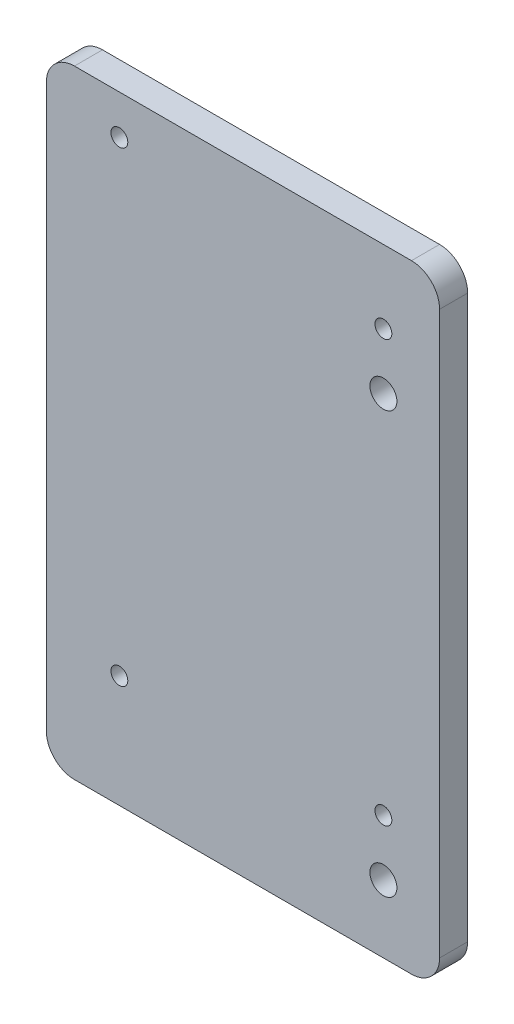
SolidWorks part; units mm, degrees
ref_plane "Front Plane" through (0, 0, 0) normal (0, 0, 1) x (1, 0, 0)
ref_plane "Top Plane" through (0, 0, 0) normal (0, 1, 0) x (1, 0, 0)
ref_plane "Right Plane" through (0, 0, 0) normal (1, 0, 0) x (0, 0, -1)
sketch "Sketch1" plane through (0, 0, 0) normal (0, 0, 1) x (1, 0, 0)
  line L0 (25, 68.3014) -> (25, -81.9854) construction
  line L1 (-35, 55) -> (35, 55)
  line L2 (-35, 55) -> (-35, -55)
  line L3 (-35, -55) -> (35, -55)
  line L4 (35, 55) -> (35, -55)
  line L5 (-35, 55) -> (35, -55) construction
  line L6 (-35, -55) -> (35, 55) construction
  line L7 (-63.581, -33) -> (92.4206, -33) construction
  line L8 (-60.7952, 42) -> (78.4919, 42) construction
  line L9 (-22, 68.3014) -> (-22, -85.2847) construction
  line L10 (-58.8108, 48) -> (82.4031, 48) construction
  line L11 (-66.295, -43) -> (105.8522, -43) construction
  line L12 (-79.5569, -35) -> (101.4075, -35) construction
  circle A0 centre (25, 42) radius 1.5
  circle A1 centre (25, -33) radius 1.5
  circle A2 centre (25, 32) radius 2.4
  circle A3 centre (25, -43) radius 2.4
  circle A4 centre (-22, 48) radius 1.5
  circle A5 centre (-22, -35) radius 1.5
  point P0 (0, 0)
  dimension "D6" = 3
  dimension "D7" = 10
  dimension "D8" = 10
  dimension "D9" = 4.8
  dimension "D1" = 110
  dimension "D2" = 70
  dimension "D3" = 10
  dimension "D4" = 22
  dimension "D5" = 75
  dimension "D10" = 47
  dimension "D11" = 6
  dimension "D12" = 83
extrude "Boss-Extrude1" add sketch "Sketch1" along normal blind 5
fillet "Fillet1" radius 5 4 edges at (35, -55, 2.5) (-35, -55, 2.5) (-35, 55, 2.5) (35, 55, 2.5)
